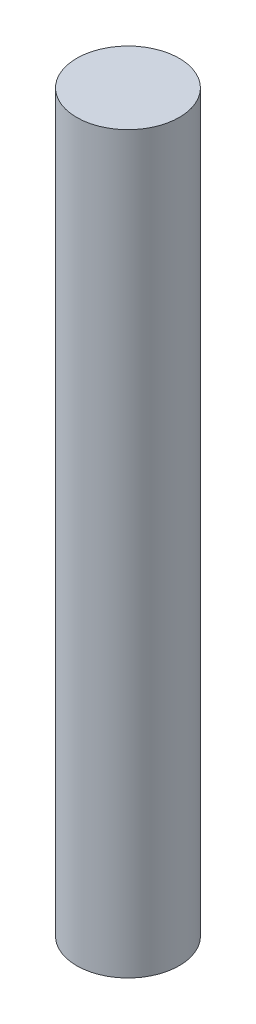
SolidWorks part; units mm, degrees
ref_plane "前视基准面" through (0, 0, 0) normal (0, 0, 1) x (1, 0, 0)
ref_plane "上视基准面" through (0, 0, 0) normal (0, 1, 0) x (1, 0, 0)
ref_plane "右视基准面" through (0, 0, 0) normal (1, 0, 0) x (0, 0, -1)
other "Configuration Table"
sketch "草图1" plane through (0, 0, 0) normal (0, 1, 0) x (1, 0, 0)
  circle A0 centre (0, 0) radius 1.5
extrude "凸台-拉伸1" add sketch "草图1" along normal blind 21.5
